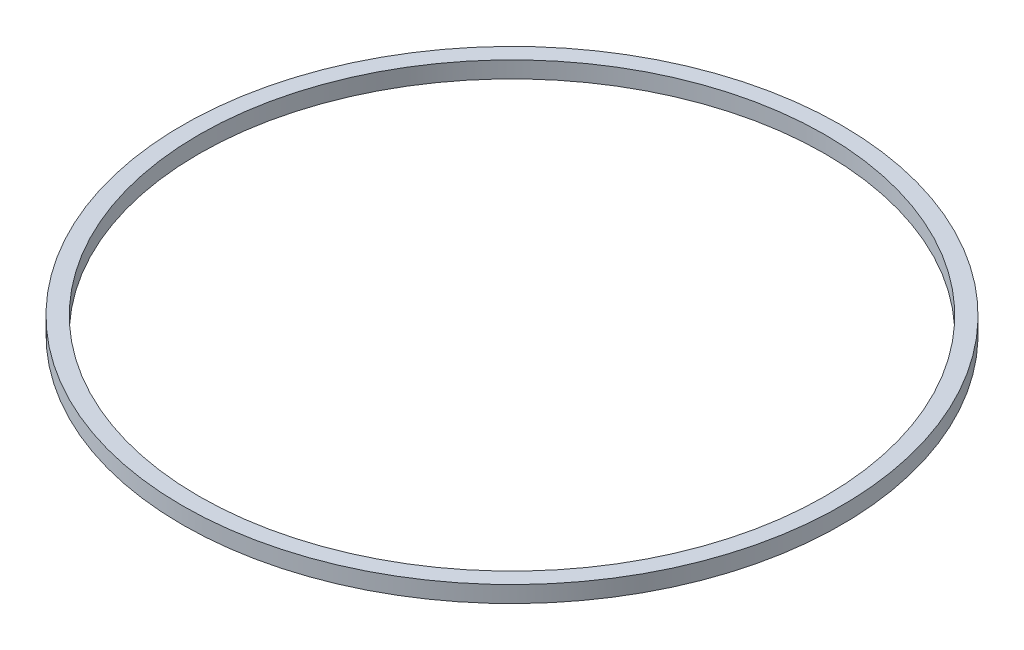
SolidWorks part; units mm, degrees
ref_plane "Front Plane" through (0, 0, 0) normal (0, 0, 1) x (1, 0, 0)
ref_plane "Top Plane" through (0, 0, 0) normal (0, 1, 0) x (1, 0, 0)
ref_plane "Right Plane" through (0, 0, 0) normal (1, 0, 0) x (0, 0, -1)
sketch "Sketch1" plane through (0, 0, 0) normal (0, 1, 0) x (1, 0, 0)
  circle A0 centre (0, 0) radius 200
  dimension "D1" = 400
extrude "Boss-Extrude1" add sketch "Sketch1" along normal blind 10
sketch "Sketch2" plane through (0, 10, 0) normal (0, 1, 0) x (1, 0, 0)
  circle A2 centre (0, 0) radius 190
  circle A3 centre (0, 0) radius 190
  dimension "D1" = 10
extrude "Cut-Extrude1" cut sketch "Sketch2" against normal through all
